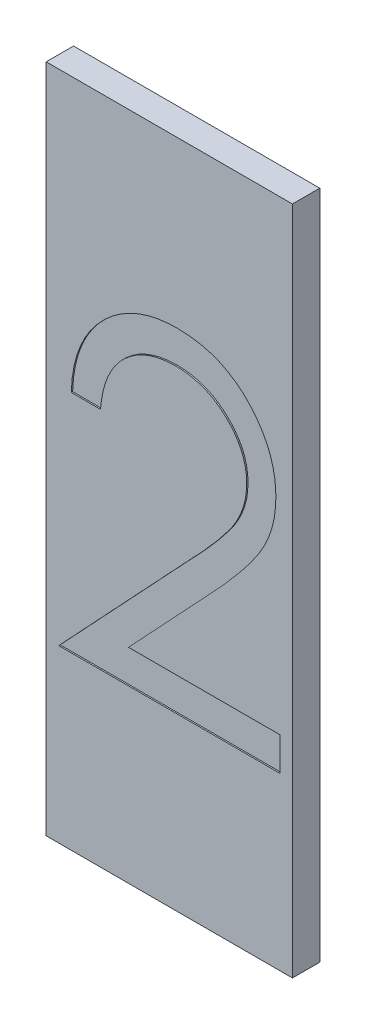
SolidWorks part; units mm, degrees
ref_plane "正面" through (0, 0, 0) normal (0, 0, 1) x (1, 0, 0)
ref_plane "平面" through (0, 0, 0) normal (0, 1, 0) x (1, 0, 0)
ref_plane "右側面" through (0, 0, 0) normal (1, 0, 0) x (0, 0, -1)
sketch "ｽｹｯﾁ1" plane through (0, 0, 0) normal (0, 0, 1) x (1, 0, 0)
  line L0 (18, 0) -> (0, 0)
  line L1 (18, 49) -> (0, 49)
  line L2 (0, 0) -> (0, 49)
  line L4 (18, 0) -> (18, 49)
extrude "ﾎﾞｽ - 押し出し1" add sketch "ｽｹｯﾁ1" along normal blind 2
sketch "ｽｹｯﾁ2" plane through (0, 0, 2) normal (0, 0, 1) x (1, 0, 0)
  text T0 "2" font "Century Gothic" height in points 90
extrude "ｶｯﾄ - 押し出し1" cut sketch "ｽｹｯﾁ2" against normal blind 0.1
